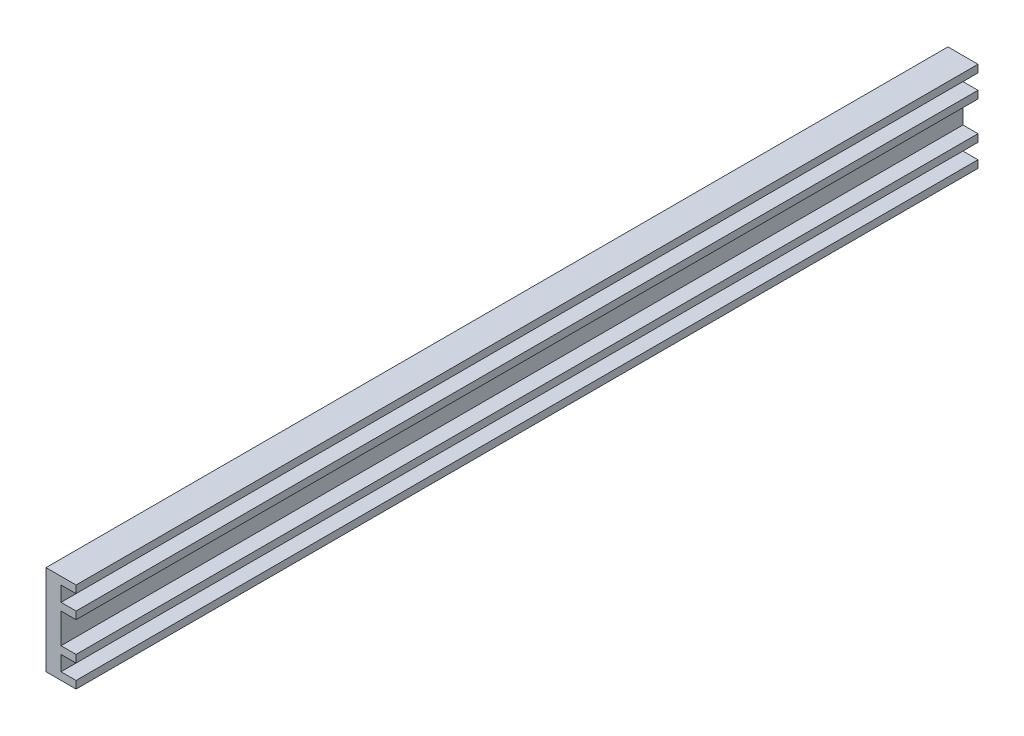
SolidWorks part; units mm, degrees
ref_plane "Front Plane" through (0, 0, 0) normal (0, 0, 1) x (1, 0, 0)
ref_plane "Top Plane" through (0, 0, 0) normal (0, 1, 0) x (1, 0, 0)
ref_plane "Right Plane" through (0, 0, 0) normal (1, 0, 0) x (0, 0, -1)
sketch "Sketch1" plane through (0, 0, 0) normal (0, 0, 1) x (1, 0, 0)
  line L1 (0, 0) -> (6.35, 0)
  line L2 (0, 0) -> (0, 19.05)
  line L3 (0, 19.05) -> (6.35, 19.05)
  line L4 (6.35, 0) -> (6.35, 19.05)
  dimension "D1" = 6.35
  dimension "D2" = 19.05
extrude "Boss-Extrude1" add sketch "Sketch1" along normal blind 190.5 contours L2 L3 L4 L1
sketch "Sketch2" plane through (6.35, 0, 0) normal (1, 0, 0) x (0, 0, -1)
  line L0 (-177.8, 0) -> (-177.8, 6.35)
  line L1 (-190.5, 0) -> (-184.15, 0)
  line L2 (-190.5, 0) -> (-190.5, 6.35)
  line L3 (-190.5, 6.35) -> (-184.15, 6.35)
  line L4 (-184.15, 0) -> (-184.15, 6.35)
  line L5 (-177.8, 0) -> (-171.45, 0)
  line L6 (-171.45, 0) -> (-171.45, 6.35)
  line L7 (-177.8, 6.35) -> (-171.45, 6.35)
  line L8 (-165.1, 0) -> (-165.1, 6.35)
  line L9 (-165.1, 0) -> (-158.75, 0)
  line L10 (-158.75, 0) -> (-158.75, 6.35)
  line L11 (-165.1, 6.35) -> (-158.75, 6.35)
  line L12 (-152.4, 0) -> (-152.4, 6.35)
  line L13 (-152.4, 0) -> (-146.05, 0)
  line L14 (-146.05, 0) -> (-146.05, 6.35)
  line L15 (-152.4, 6.35) -> (-146.05, 6.35)
  line L16 (-139.7, 0) -> (-139.7, 6.35)
  line L17 (-139.7, 0) -> (-133.35, 0)
  line L18 (-133.35, 0) -> (-133.35, 6.35)
  line L19 (-139.7, 6.35) -> (-133.35, 6.35)
  line L20 (-127, 0) -> (-127, 6.35)
  line L21 (-127, 0) -> (-120.65, 0)
  line L22 (-120.65, 0) -> (-120.65, 6.35)
  line L23 (-127, 6.35) -> (-120.65, 6.35)
  line L24 (-114.3, 0) -> (-114.3, 6.35)
  line L25 (-114.3, 0) -> (-107.95, 0)
  line L26 (-107.95, 0) -> (-107.95, 6.35)
  line L27 (-114.3, 6.35) -> (-107.95, 6.35)
  line L28 (-101.6, 0) -> (-101.6, 6.35)
  line L29 (-101.6, 0) -> (-95.25, 0)
  line L30 (-95.25, 0) -> (-95.25, 6.35)
  line L31 (-101.6, 6.35) -> (-95.25, 6.35)
  line L32 (-88.9, 0) -> (-88.9, 6.35)
  line L33 (-88.9, 0) -> (-82.55, 0)
  line L34 (-82.55, 0) -> (-82.55, 6.35)
  line L35 (-88.9, 6.35) -> (-82.55, 6.35)
  line L36 (-76.2, 0) -> (-76.2, 6.35)
  line L37 (-76.2, 0) -> (-69.85, 0)
  line L38 (-69.85, 0) -> (-69.85, 6.35)
  line L39 (-76.2, 6.35) -> (-69.85, 6.35)
  line L40 (-63.5, 0) -> (-63.5, 6.35)
  line L41 (-63.5, 0) -> (-57.15, 0)
  line L42 (-57.15, 0) -> (-57.15, 6.35)
  line L43 (-63.5, 6.35) -> (-57.15, 6.35)
  line L44 (-50.8, 0) -> (-50.8, 6.35)
  line L45 (-50.8, 0) -> (-44.45, 0)
  line L46 (-44.45, 0) -> (-44.45, 6.35)
  line L47 (-50.8, 6.35) -> (-44.45, 6.35)
  line L48 (-38.1, 0) -> (-38.1, 6.35)
  line L49 (-38.1, 0) -> (-31.75, 0)
  line L50 (-31.75, 0) -> (-31.75, 6.35)
  line L51 (-38.1, 6.35) -> (-31.75, 6.35)
  line L52 (-25.4, 0) -> (-25.4, 6.35)
  line L53 (-25.4, 0) -> (-19.05, 0)
  line L54 (-19.05, 0) -> (-19.05, 6.35)
  line L55 (-25.4, 6.35) -> (-19.05, 6.35)
  line L56 (-12.7, 0) -> (-12.7, 6.35)
  line L57 (-12.7, 0) -> (-6.35, 0)
  line L58 (-6.35, 0) -> (-6.35, 6.35)
  line L59 (-12.7, 6.35) -> (-6.35, 6.35)
  point P5 (-187.325, 6.35)
  dimension "D1" = 6.35
  dimension "D2" = 6.35
  dimension "D3" = 15
extrude "Cut-Extrude1" [suppressed] cut sketch "Sketch2" against normal up to next
sketch "Sketch3" plane through (0, 0, 190.5) normal (0, 0, 1) x (1, 0, 0)
  line L0 (6.35, 0) -> (6.35, 19.05) construction
  line L1 (6.35, 12.7) -> (3.175, 12.7)
  line L2 (6.35, 12.7) -> (6.35, 6.35)
  line L3 (6.35, 6.35) -> (3.175, 6.35)
  line L4 (3.175, 12.7) -> (3.175, 6.35)
  line L5 (0, 19.05) -> (6.35, 19.05) construction
  line L6 (6.35, 17.4625) -> (3.175, 17.4625)
  line L7 (6.35, 17.4625) -> (6.35, 14.2875)
  line L8 (6.35, 14.2875) -> (3.175, 14.2875)
  line L9 (3.175, 17.4625) -> (3.175, 14.2875)
  line L10 (6.35, 4.7625) -> (3.175, 4.7625)
  line L11 (6.35, 4.7625) -> (6.35, 1.5875)
  line L12 (6.35, 1.5875) -> (3.175, 1.5875)
  line L13 (3.175, 4.7625) -> (3.175, 1.5875)
  dimension "D1" = 3.175
  dimension "D2" = 3.175
  dimension "D3" = 3.175
  dimension "D4" = 1.5875
  dimension "D5" = 1.5875
  dimension "D6" = 1.5875
  dimension "D7" = 3.175
  dimension "D8" = 6.35
extrude "Cut-Extrude2" cut sketch "Sketch3" against normal up to next
